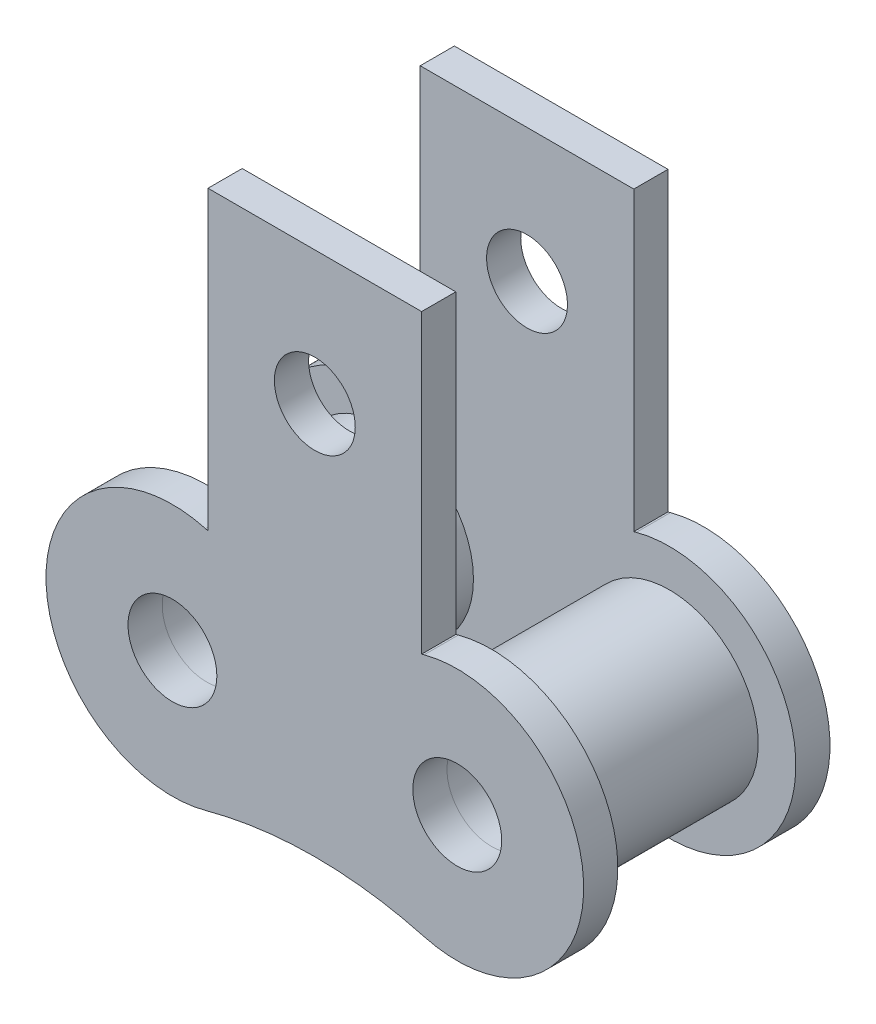
SolidWorks part; units mm, degrees
ref_plane "Front Plane" through (0, 0, 0) normal (0, 0, 1) x (1, 0, 0)
ref_plane "Top Plane" through (0, 0, 0) normal (0, 1, 0) x (1, 0, 0)
ref_plane "Right Plane" through (0, 0, 0) normal (1, 0, 0) x (0, 0, -1)
sketch "Sketch1" plane through (0, 0, 0) normal (0, 0, 1) x (1, 0, 0)
  line L0 (-6.35, 0) -> (6.35, 0) construction
  line L1 (-6.35, 5.6388) -> (-6.35, -5.6388) construction
  line L2 (0, -4.793) -> (0, 4.793) construction
  line L4 (-4.7625, 18.6436) -> (4.7625, 18.6436) construction
  line L5 (-6.35, -5.6388) -> (6.35, -5.6388) construction
  line L6 (6.35, 5.6388) -> (6.35, -5.6388)
  circle A0 centre (-6.35, 0) radius 3.9624 construction
  circle A1 centre (6.35, 0) radius 3.9624 construction
  circle A2 centre (-6.35, 0) radius 1.9812
  circle A3 centre (6.35, 0) radius 1.9812
  arc A4 (-4.874, 5.4422) -> (-4.874, -5.4422) centre (-6.35, 0) ccw
  arc A5 (4.874, -5.4422) -> (4.874, 5.4422) centre (6.35, 0) ccw
  arc A9 (4.874, -5.4422) -> (-4.874, -5.4422) centre (0, -23.4134) ccw
  point P17 (0, 18.6436)
  dimension "Roller Dia" = 7.9248
  dimension "Pin Dia" = 3.9624
  dimension "Pitch" = 12.7
  dimension "D1" = 9.586
sketch "Sketch2" plane through (0, 0, 0) normal (0, 1, 0) x (1, 0, 0)
  line L0 (0, 3.9688) -> (0, -3.9688) construction
  point P2 (0, -5.4928)
  point P4 (0, 5.4928)
  point P5 (0, 5.5436)
  point P6 (0, 7.0676)
  dimension "W" = 7.9375
  dimension "T" = 1.524
  dimension "D1" = 1.524
  dimension "D2" = 1.524
  dimension "D3" = 0.0508
ref_plane "Plane1" through (0, 0, 3.9688) normal (0, 0, 1) x (1, 0, 0)
ref_plane "Plane2" through (0, 0, -5.5436) normal (0, 0, 1) x (1, 0, 0)
sketch "Sketch4" plane through (0, 0, 0) normal (0, 0, 1) x (1, 0, 0)
  circle A0 centre (-6.35, 0) radius 3.9624 construction
  circle A1 centre (-6.35, 0) radius 3.9624 construction
  circle A2 centre (6.35, 0) radius 3.9624 construction
  circle A3 centre (6.35, 0) radius 3.9624
  circle A4 centre (-6.35, 0) radius 2.0066 construction
  circle A5 centre (6.35, 0) radius 2.0066
  dimension "D1" = 4.0132
  dimension "D2" = 4.0132
extrude "Boss-Extrude1" add sketch "Sketch4" along normal mid plane 7.9375
sketch "Sketch5" plane through (0, 0, 3.9688) normal (0, 0, 1) x (1, 0, 0)
  arc A0 (-4.874, 5.4422) -> (-4.874, -5.4422) centre (-6.35, 0) ccw construction
  circle A2 centre (-6.35, 0) radius 1.9812 construction
  arc A3 (4.874, -5.4422) -> (4.874, 5.4422) centre (6.35, 0) ccw construction
  circle A4 centre (6.35, 0) radius 1.9812 construction
  arc A6 (-4.874, 5.4422) -> (-4.874, -5.4422) centre (-6.35, 0) ccw
  arc A7 (-4.874, 5.4422) -> (4.874, 5.4422) centre (0, 23.4134) ccw
  circle A8 centre (-6.35, 0) radius 1.9812
  arc A9 (4.874, -5.4422) -> (4.874, 5.4422) centre (6.35, 0) ccw
  circle A10 centre (6.35, 0) radius 1.9812
  arc A11 (4.874, -5.4422) -> (-4.874, -5.4422) centre (0, -23.4134) ccw construction
  arc A12 (4.874, -5.4422) -> (-4.874, -5.4422) centre (0, -23.4134) ccw
extrude "Boss-Extrude2" add sketch "Sketch5" along normal up to vertex (1.524 mm away) separate body up to point (0, 0, 5.4928)
pattern_linear "LPattern1" count 2 spacing 12.7 along (-1, 0, 0) of bodies 102
sketch "Sketch7" plane through (0, 0, -3.9688) normal (0, 0, 1) x (1, 0, 0)
  line L0 (-6.35, 5.6388) -> (-6.35, -5.6388) construction
  arc A0 (4.874, -5.4422) -> (4.874, 5.4422) centre (6.35, 0) ccw
  arc A1 (-4.874, 5.4422) -> (-4.874, -5.4422) centre (-6.35, 0) ccw
  arc A2 (4.874, -5.4422) -> (4.874, 5.4422) centre (6.35, 0) ccw construction
  circle A3 centre (-6.35, 0) radius 3.9624 construction
  arc A5 (4.874, 5.4422) -> (-4.874, 5.4422) centre (0, 23.4134) cw
  arc A6 (-4.874, 5.4422) -> (-4.874, -5.4422) centre (-6.35, 0) ccw construction
  circle A7 centre (6.35, 0) radius 1.9812 construction
  circle A8 centre (6.35, 0) radius 1.9812
  circle A9 centre (-6.35, 0) radius 1.9812
  arc A10 (-4.874, -5.4422) -> (4.874, -5.4422) centre (0, -23.4134) cw
  arc A12 (4.874, -5.4422) -> (-4.874, -5.4422) centre (0, -23.4134) ccw construction
extrude "Boss-Extrude3" add sketch "Sketch7" against normal blind 1.524 separate body
sketch "Sketch13" plane through (0, 17.1069, -5.4928) normal (0, 0, -1) x (-1, 0, 0)
  line L0 (-11.9888, -17.1069) -> (11.9888, -17.1069) construction
  line L1 (0, -4.4069) -> (0, -17.1069) construction
  line L2 (-4.7625, -12.3139) -> (-4.7625, 1.5367)
  line L3 (-4.7625, 1.5367) -> (4.7625, 1.5367)
  line L4 (4.7625, -12.3139) -> (4.7625, 1.5367)
  line L5 (4.7625, 1.5367) -> (-4.7625, 1.5367) construction
  line L12 (0, -4.4069) -> (0, 1.5367) construction
  line L13 (-4.7625, -12.3139) -> (4.7625, -12.3139)
  circle A0 centre (0, -4.4069) radius 1.8034
  arc A1 (-4.874, -11.6647) -> (4.874, -11.6647) centre (0, 6.3065) ccw construction
  arc A2 (-4.874, -11.6647) -> (-4.874, -22.5491) centre (-6.35, -17.1069) ccw construction
  dimension "O" = 3.6068
  dimension "R" = 12.7
extrude "Boss-Extrude6" add sketch "Sketch13" against normal blind 1.524
sketch "Sketch14" plane through (0, 0, 3.9688) normal (0, 0, -1) x (-1, 0, 0)
  line L4 (-4.7625, 18.6436) -> (-4.7625, 4.793)
  line L5 (4.7625, 18.6436) -> (-4.7625, 18.6436)
  line L6 (4.7625, 4.793) -> (4.7625, 18.6436)
  line L7 (-4.7625, 4.793) -> (4.7625, 4.793)
  line L8 (-4.7625, 18.6436) -> (-4.7625, 4.793)
  line L9 (4.7625, 18.6436) -> (-4.7625, 18.6436)
  line L10 (4.7625, 4.793) -> (4.7625, 18.6436)
  line L11 (-4.7625, 4.793) -> (4.7625, 4.793)
  circle A1 centre (0, 12.7) radius 1.8034
  circle A2 centre (0, 12.7) radius 1.8034
  dimension "D1" = 0
  dimension "D2" = 0
extrude "Boss-Extrude7" add sketch "Sketch14" against normal up to surface (1.524 mm away) up to face at (-4.3688, 0, 5.4928)
equation "\"D1@Sketch2\" = \"T@Sketch2\""
equation "\"D1@Sketch4\" = \"Pin Dia@Sketch1\"+.002"
equation "\"D2@Sketch4\" = \"D1@Sketch4\""
equation "\"D1@Boss-Extrude1\" = \"W@Sketch2\""
equation "\"D2@Sketch2\" = \"T@Sketch2\""
equation "\"D3@LPattern1\" = \"Pitch@Sketch1\""
equation "\"D1@Boss-Extrude6\" = \"T@Sketch2\""
equation "\"D1@Sketch1\" = (\"Z@Sketch1\"*2)*.85"
equation "\"D1@Boss-Extrude3\" = \"T@Sketch2\""
